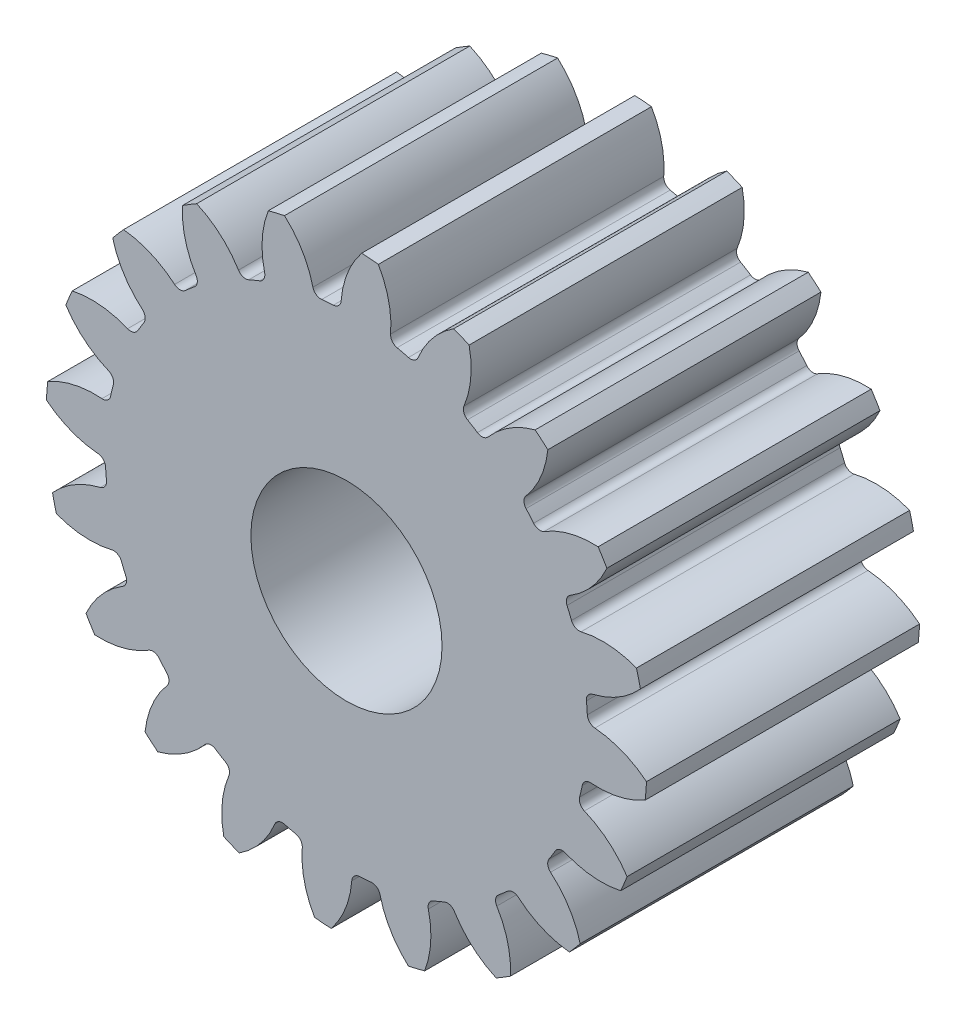
SolidWorks part; units mm, degrees
ref_plane "Alzado" through (0, 0, 0) normal (0, 0, 1) x (1, 0, 0)
ref_plane "Planta" through (0, 0, 0) normal (0, 1, 0) x (1, 0, 0)
ref_plane "Vista lateral" through (0, 0, 0) normal (1, 0, 0) x (0, 0, -1)
sketch "Croquis1" plane through (0, 0, 0) normal (0, 0, 1) x (1, 0, 0)
  line L0 (0, 31.7905) -> (0, 0) construction
  line L1 (0, 0) -> (2.4849, 31.5403) construction
  line L2 (0, 10) -> (3.214, 8.8302) construction
  line L3 (1.5659, 9.8766) -> (-1.7916, 9.2245) construction
  circle A0 centre (0, 0) radius 9.3969 construction
  circle A1 centre (0, 0) radius 10 construction
  circle A2 centre (0, 0) radius 11 construction
  arc A3 (-0.2063, 8.8306) -> (1.5866, 8.6893) centre (0, 0) ccw
  arc A4 (0.5585, 10.9858) -> (-0.2063, 8.8306) centre (3.214, 8.8302) ccw
  arc A5 (1.1687, 10.9377) -> (1.5866, 8.6893) centre (-1.7916, 9.2245) cw
  arc A6 (1.1687, 10.9377) -> (0.5585, 10.9858) centre (0, 0) ccw
  circle A8 centre (0, 0) radius 3.5
  dimension "D1" = 22
  dimension "D2" = 20
  dimension "D3" = 18.7938
  dimension "D4" = 17.666
  dimension "D6" = 7
  dimension "D5" = 1.5708
extrude "Saliente-Extruir1" add sketch "Croquis1" along normal blind 10
fillet "Redondeo1" radius 0.3 2 edges at (-0.2063, 8.8306, 5) (1.5866, 8.6893, 5)
pattern_circular "MatrizC1" count 20 over 360 about axis through (0, 0, 0) along (0, 0, 1) of "Saliente-Extruir1", "Redondeo1"
